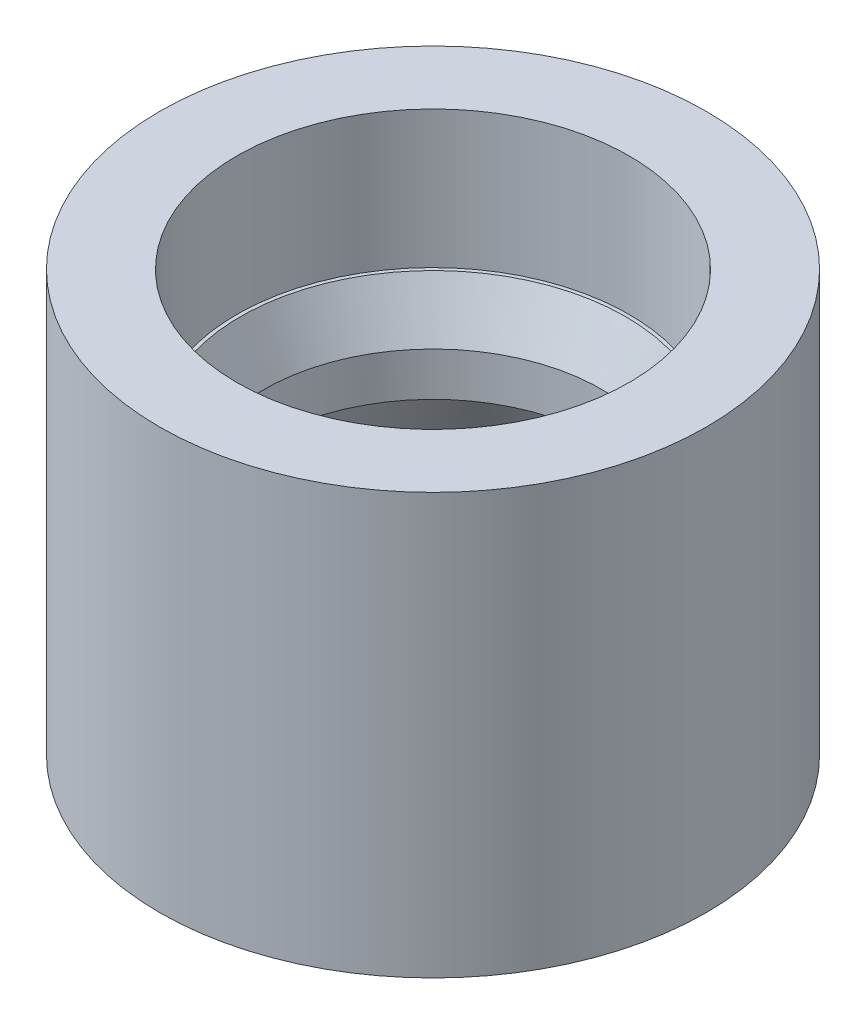
SolidWorks part; units mm, degrees
ref_plane "Front Plane" through (0, 0, 0) normal (0, 0, 1) x (1, 0, 0)
ref_plane "Top Plane" through (0, 0, 0) normal (0, 1, 0) x (1, 0, 0)
ref_plane "Right Plane" through (0, 0, 0) normal (1, 0, 0) x (0, 0, -1)
sketch "Sketch1" plane through (0, 0, 0) normal (0, 1, 0) x (1, 0, 0)
  circle A0 centre (0, 0) radius 12
  circle A1 centre (0, 0) radius 5
extrude "Boss-Extrude1" add sketch "Sketch1" along normal blind 15
sketch "Sketch2" plane through (0, 0, 0) normal (0, -1, 0) x (1, 0, 0)
  circle A0 centre (0, 0) radius 7
extrude "Cut-Extrude1" cut sketch "Sketch2" against normal blind 5.1
sketch "Sketch3" plane through (0, 15, 0) normal (0, 1, 0) x (1, 0, 0)
  circle A0 centre (0, 0) radius 7
extrude "Cut-Extrude2" cut sketch "Sketch3" against normal blind 5.1
sketch "Sketch4" plane through (0, 9.9, 0) normal (0, 1, 0) x (1, 0, 0)
  circle A0 centre (0, 0) radius 5
  circle A1 centre (0, 0) radius 3
extrude "Boss-Extrude2" add sketch "Sketch4" against normal up to surface (4.8 mm away) up to face at (0, 5.1, -5)
sketch "Sketch5" plane through (0, 0, 0) normal (0, -1, 0) x (1, 0, 0)
  circle A0 centre (0, 0) radius 10
  circle A1 centre (0, 0) radius 17.6442
extrude "Cut-Extrude3" cut sketch "Sketch5" against normal blind 17.1
sketch "Sketch6" plane through (0, 0, 0) normal (0, -1, 0) x (1, 0, 0)
  circle A0 centre (0, 0) radius 7.1
extrude "Cut-Extrude4" cut sketch "Sketch6" against normal up to surface (5.1 mm away)
sketch "Sketch7" plane through (0, 15, 0) normal (0, 1, 0) x (1, 0, 0)
  circle A0 centre (0, 0) radius 7.1
extrude "Cut-Extrude5" cut sketch "Sketch7" against normal up to surface (5.1 mm away)
sketch "Sketch8" plane through (0, 0, 0) normal (0, -1, 0) x (1, 0, 0)
  circle A1 centre (0, 0) radius 14.8351
  circle A2 centre (0, 0) radius 9.75
extrude "Cut-Extrude7" cut sketch "Sketch8" against normal blind 26
sketch "Sketch9" plane through (0, 9.9, 0) normal (0, 1, 0) x (1, 0, 0)
  circle A0 centre (0, 0) radius 6.0215
extrude "Cut-Extrude8" cut sketch "Sketch9" against normal blind 10
sketch "Sketch10" plane through (0, 5.1, 0) normal (0, -1, 0) x (1, 0, 0)
  circle A0 centre (0, 0) radius 7.1
  circle A1 centre (0, 0) radius 6.0215
extrude "Boss-Extrude3" add sketch "Sketch10" along normal blind 0.2
sketch "Sketch11" plane through (0, 9.9, 0) normal (0, 1, 0) x (1, 0, 0)
  circle A0 centre (0, 0) radius 7.1
  circle A1 centre (0, 0) radius 6.0215
extrude "Boss-Extrude4" add sketch "Sketch11" along normal blind 0.2
chamfer "Chamfer2" distance 0.85 angle 65 2 edges at (0, 10.1, 6.0215) (0, 4.9, -6.0215)
sketch "Sketch12" plane through (0, 15, 0) normal (0, 1, 0) x (1, 0, 0)
  circle A0 centre (0, 0) radius 9.75 construction
  circle A1 centre (0, 0) radius 9.75
  circle A2 centre (0, 0) radius 7
extrude "Boss-Extrude5" add sketch "Sketch12" against normal up to surface (15 mm away) up to face at (0, 0, -7.1)
